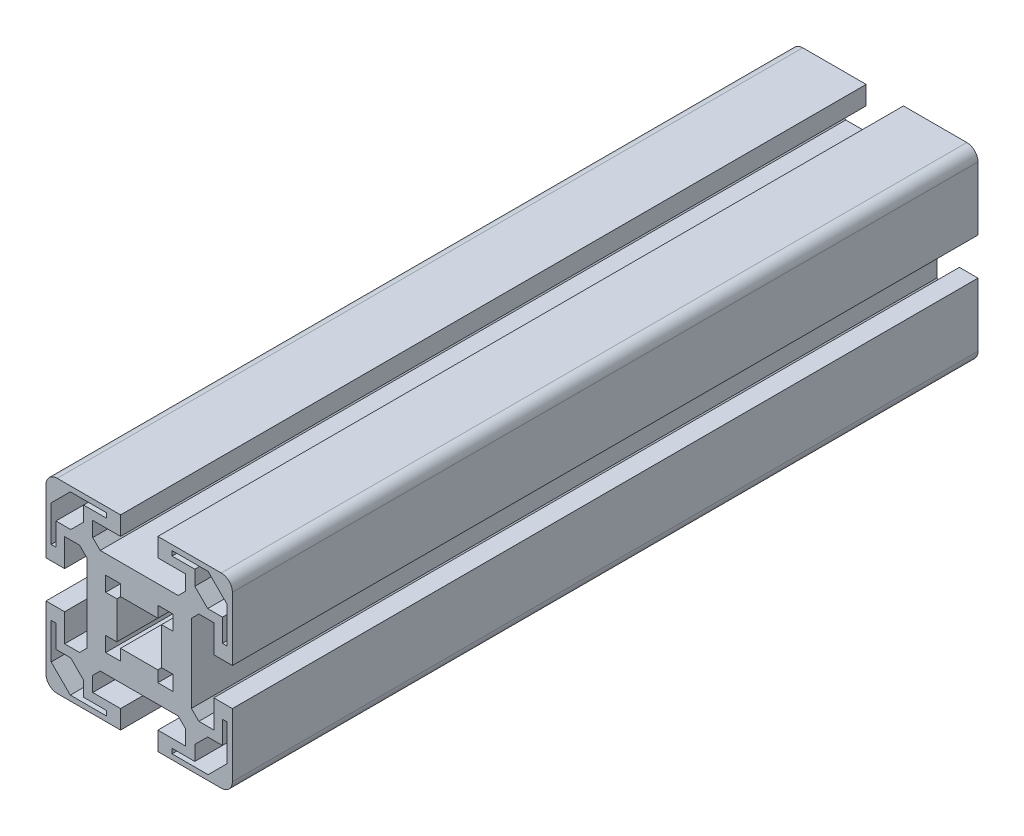
SolidWorks part; units mm, degrees
ref_plane "Alzado" through (0, 0, 0) normal (0, 0, 1) x (1, 0, 0)
ref_plane "Planta" through (0, 0, 0) normal (0, 1, 0) x (1, 0, 0)
ref_plane "Vista lateral" through (0, 0, 0) normal (1, 0, 0) x (0, 0, -1)
sketch "Croquis1" plane through (0, 0, 0) normal (0, 0, 1) x (1, 0, 0)
  line L0 (0, 0) -> (23829.6444, 0) construction
  line L1 (0, 0) -> (0, 23829.6444) construction
  line L2 (5, 25) -> (22, 25)
  line L3 (23.6123, 18.4785) -> (18.4785, 23.6123)
  line L4 (5, 25) -> (5, 20)
  line L5 (5, 20) -> (12.4645, 20)
  line L6 (12.4645, 20) -> (12.4645, 16)
  line L7 (12.4645, 16) -> (10.4645, 14)
  line L8 (10.4645, 14) -> (0, 14)
  line L9 (0, 6) -> (5, 6)
  line L10 (5, 6) -> (5, 9)
  line L11 (5, 9) -> (9, 9)
  line L12 (22.3289, 14.9134) -> (18.3598, 14.9134)
  line L13 (22.3289, 8.8172) -> (22.3289, 14.9134)
  line L14 (23.6123, 8.8172) -> (22.3289, 8.8172)
  line L15 (18.4785, 23.6123) -> (8.8172, 23.6123)
  line L16 (0, 0) -> (38.8156, 38.8156) construction
  line L17 (8.8172, 23.6123) -> (8.8172, 22.3289)
  line L18 (8.8172, 22.3289) -> (14.9134, 22.3289)
  line L19 (14.9134, 22.3289) -> (14.9134, 18.3598)
  line L20 (14.9134, 18.3598) -> (18.3598, 14.9134)
  line L21 (23.6123, 18.4785) -> (23.6123, 8.8172)
  line L22 (9, 5) -> (9, 9)
  line L23 (6, 5) -> (9, 5)
  line L24 (6, 0) -> (6, 5)
  line L25 (14, 10.4645) -> (14, 0)
  line L26 (16, 12.4645) -> (14, 10.4645)
  line L27 (20, 12.4645) -> (16, 12.4645)
  line L28 (20, 5) -> (20, 12.4645)
  line L29 (25, 5) -> (20, 5)
  line L30 (25, 5) -> (25, 22)
  line L31 (0, 14) -> (0, 6)
  line L32 (6, 0) -> (14, 0)
  arc A0 (22, 25) -> (25, 22) centre (22, 22) cw
  point P22 (16.6366, 16.6366)
  point P43 (21.0454, 21.0454)
  dimension "D3" = 3
  dimension "D9" = 12
  dimension "D1" = 5
  dimension "D2" = 50
  dimension "D4" = 10
  dimension "D5" = 6
  dimension "D6" = 45
  dimension "D7" = 5
  dimension "D8" = 4
  dimension "D10" = 6
  dimension "D11" = 5
extrude "Saliente-Extruir1" add sketch "Croquis1" along normal mid plane 200
mirror "Simetría1" about plane through (0, 14, 100) normal (1, 0, 0) of "Saliente-Extruir1"
mirror "Simetría7" about plane through (6, 0, 100) normal (0, 1, 0) of bodies 102
